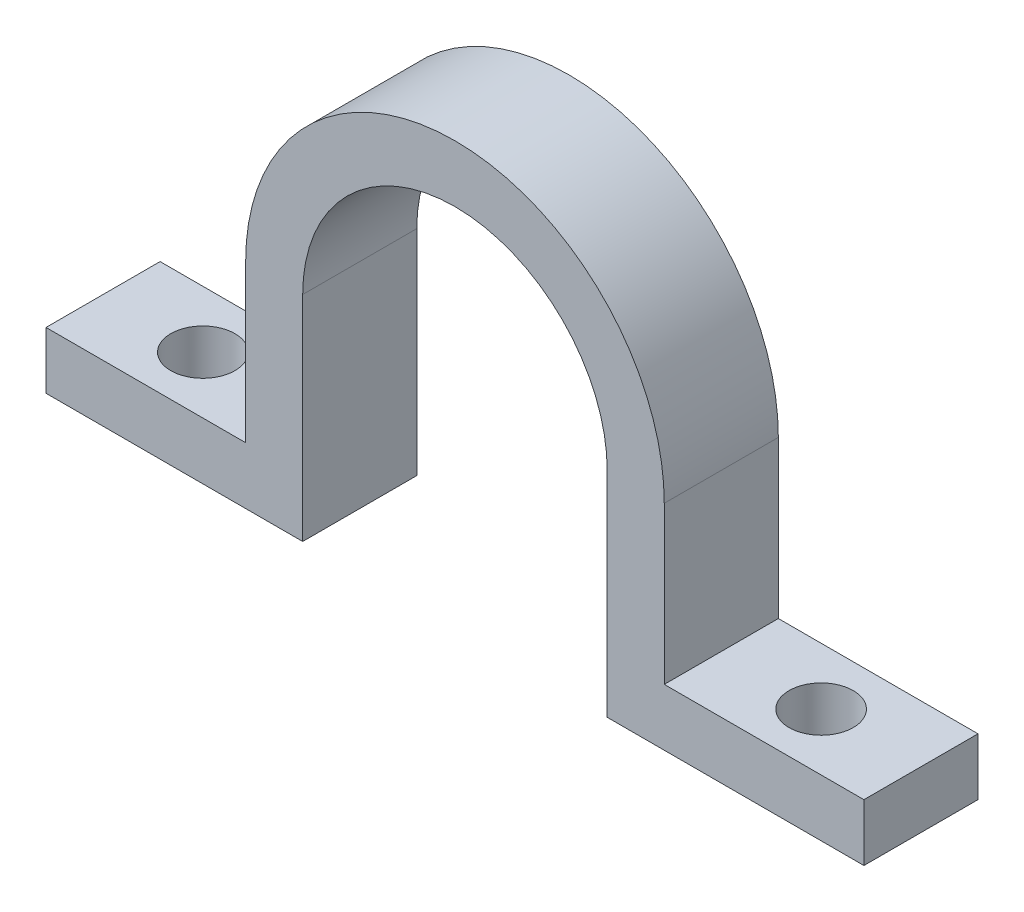
SolidWorks part; units mm, degrees
material "PETG"
ref_plane "Front Plane" through (0, 0, 0) normal (0, 0, 1) x (1, 0, 0)
ref_plane "Top Plane" through (0, 0, 0) normal (0, 1, 0) x (1, 0, 0)
ref_plane "Right Plane" through (0, 0, 0) normal (1, 0, 0) x (0, 0, -1)
other "Configuration Table"
sketch "Sketch1" plane through (0, 0, 0) normal (0, 0, 1) x (1, 0, 0)
  line L0 (-28.6775, 0) -> (-10.6775, 0)
  line L1 (-10.6775, 0) -> (-10.6775, 15)
  line L2 (10.6775, 15) -> (10.6775, 0)
  line L3 (10.6775, 0) -> (28.6775, 0)
  line L4 (28.6775, 0) -> (28.6775, 4)
  line L5 (28.6775, 4) -> (14.6775, 4)
  line L6 (14.6775, 4) -> (14.6775, 15)
  line L7 (-14.6775, 15) -> (-14.6775, 4)
  line L8 (-14.6775, 4) -> (-28.6775, 4)
  line L9 (-28.6775, 4) -> (-28.6775, 0)
  arc A0 (-10.6775, 15) -> (10.6775, 15) centre (0, 15) cw
  arc A1 (14.6775, 15) -> (-14.6775, 15) centre (0, 15) ccw
extrude "Strap" add sketch "Sketch1" along normal mid plane 8
sketch "Sketch2" plane through (0, 0, 0) normal (0, 1, 0) x (1, 0, 0)
  circle A0 centre (-21.6775, 0) radius 2.25
  circle A1 centre (21.6775, 0) radius 2.25
  dimension "D1" = 4.5
  dimension "D2" = 4.5
extrude "Ear_Holes_M4" cut sketch "Sketch2" along normal blind 5 from offset 0.5
equation "\"Jar_OD\"= 90  'ASSUMED - Part C fallback - jar outer diameter"
equation "\"Jar_H\"= 120  'ASSUMED - Part C fallback - jar height"
equation "\"Pump_L\"= 45  'ASSUMED - Part C fallback"
equation "\"Pump_W\"= 24  'ASSUMED - Part C fallback"
equation "\"Pump_H\"= 33  'ASSUMED - Part C fallback"
equation "\"Pump_Outlet_OD\"= 7.5  'ASSUMED - Part C fallback"
equation "\"Tube_OD\"= 8  'ASSUMED - Part C fallback"
equation "\"Tube_ID\"= 6  'ASSUMED - Part C fallback"
equation "\"TDS_Body_Dia\"= 12  'ASSUMED - Part C fallback"
equation "\"TDS_Wet_Len\"= 45  'ASSUMED - Part C fallback - length in water"
equation "\"DS_Tube_Dia\"= 6  'ASSUMED - Part C fallback"
equation "\"DS_Tube_Len\"= 50  'ASSUMED - Part C fallback"
equation "\"ORP_Body_Dia\"= 12  'ASSUMED - Part C fallback"
equation "\"ORP_Body_Len\"= 150  'ASSUMED - Part C fallback"
equation "\"ORP_Cap_Dia\"= 16  'ASSUMED - Part C fallback"
equation "\"Turb_W\"= 33  'ASSUMED - Part C fallback - head width"
equation "\"Turb_D\"= 28  'ASSUMED - Part C fallback - head depth"
equation "\"Turb_H\"= 30  'ASSUMED - Part C fallback - head height"
equation "\"Turb_Slot_W\"= 10  'ASSUMED - Part C fallback - slot width"
equation "\"Flow_L\"= 62  'ASSUMED - Part C fallback YF-S201"
equation "\"Flow_W\"= 36  'ASSUMED - Part C fallback"
equation "\"Flow_H\"= 35  'ASSUMED - Part C fallback"
equation "\"Thread_G12_OD\"= 20.955  'ASSUMED - Part C fallback thread G1/2 (major diameter)"
equation "\"Valve_L\"= 75  'ASSUMED - Part C fallback"
equation "\"Valve_W\"= 45  'ASSUMED - Part C fallback"
equation "\"Valve_H\"= 60  'ASSUMED - Part C fallback"
equation "\"Tee_L\"= 40  'ASSUMED - Part C fallback - overall length"
equation "\"Tee_Branch_L\"= 25  'ASSUMED - Part C fallback"
equation "\"Tee_OD\"= 12  'ASSUMED - Part C fallback"
equation "\"Cuv_W\"= 12.5  'ASSUMED - Part C fallback"
equation "\"Cuv_D\"= 12.5  'ASSUMED - Part C fallback"
equation "\"Cuv_H\"= 45  'ASSUMED - Part C fallback"
equation "\"LED_Board_L\"= 20  'ASSUMED - Part C fallback"
equation "\"LED_Board_W\"= 20  'ASSUMED - Part C fallback - LED at centre"
equation "\"GUVA_L\"= 20  'ASSUMED - Part C fallback"
equation "\"GUVA_W\"= 12  'ASSUMED - Part C fallback - sensor at centre"
equation "\"Reed_L\"= 27  'ASSUMED - Part C fallback MC-38 half"
equation "\"Reed_W\"= 14  'ASSUMED - Part C fallback"
equation "\"Reed_H\"= 8  'ASSUMED - Part C fallback"
equation "\"ESP_L\"= 51  'ASSUMED - Part C fallback"
equation "\"ESP_W\"= 28  'ASSUMED - Part C fallback"
equation "\"TFT_L\"= 58  'ASSUMED - Part C fallback - board"
equation "\"TFT_W\"= 35  'ASSUMED - Part C fallback - board"
equation "\"TFT_Win_L\"= 35  'ASSUMED - Part C fallback - visible window"
equation "\"TFT_Win_W\"= 28  'ASSUMED - Part C fallback - visible window"
equation "\"Relay_L\"= 50  'ASSUMED - Part C fallback"
equation "\"Relay_W\"= 26  'ASSUMED - Part C fallback"
equation "\"Relay_H\"= 19  'ASSUMED - Part C fallback"
equation "\"Mosfet_L\"= 34  'ASSUMED - Part C fallback"
equation "\"Mosfet_W\"= 17  'ASSUMED - Part C fallback"
equation "\"Mosfet_H\"= 12  'ASSUMED - Part C fallback"
equation "\"TDS_Board_L\"= 42  'ASSUMED - Part C fallback"
equation "\"TDS_Board_W\"= 32  'ASSUMED - Part C fallback"
equation "\"Turb_Board_L\"= 38  'ASSUMED - Part C fallback"
equation "\"Turb_Board_W\"= 28  'ASSUMED - Part C fallback"
equation "\"BNC_Thread_Dia\"= 9.5  'ASSUMED - Part C fallback"
equation "\"Plate_L\"= 420  'ASSUMED - Part C fallback"
equation "\"Plate_W\"= 297  'ASSUMED - Part C fallback"
equation "\"Plate_T\"= 6  'ASSUMED - Part C fallback"
equation "\"Probe_Clr\"= 0.3  'DESIGN VALUE - Part C rule 3 - printed probe hole = diameter + 0.3"
equation "\"Cuv_Clr\"= 0.2  'DESIGN VALUE - Part C rule 3 - cuvette pocket = size + 0.2"
equation "\"Label_H\"= 0.6  'DESIGN VALUE - Part D - raised label height"
